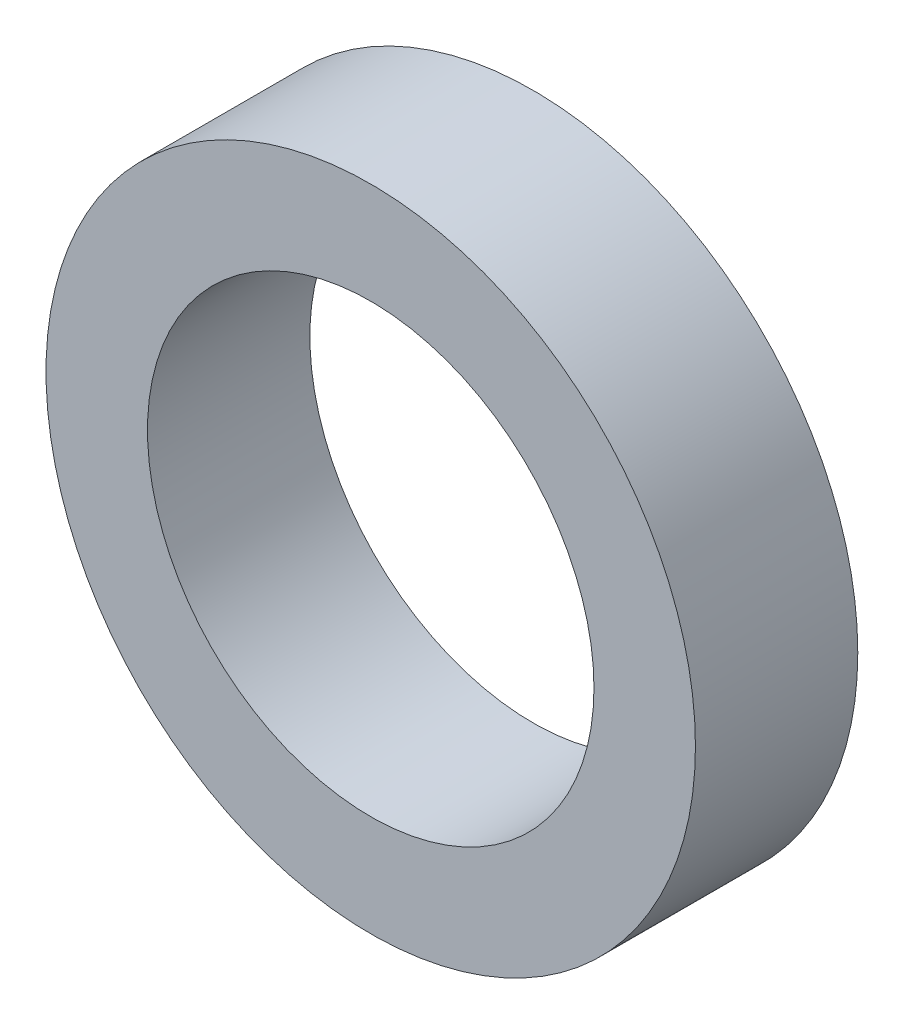
SolidWorks part; units mm, degrees
ref_plane "Front Plane" through (0, 0, 0) normal (0, 0, 1) x (1, 0, 0)
ref_plane "Top Plane" through (0, 0, 0) normal (0, 1, 0) x (1, 0, 0)
ref_plane "Right Plane" through (0, 0, 0) normal (1, 0, 0) x (0, 0, -1)
sketch "Sketch1" plane through (0, 0, 0) normal (0, 0, 1) x (1, 0, 0)
  circle A0 centre (0, 0) radius 4
  dimension "D1" = 8
extrude "Boss-Extrude1" add sketch "Sketch1" along normal blind 2
sketch "Sketch2" plane through (0, 0, 2) normal (0, 0, 1) x (1, 0, 0)
  circle A0 centre (0, 0) radius 2.75
  dimension "D1" = 5.5
extrude "Cut-Extrude1" cut sketch "Sketch2" against normal through all
